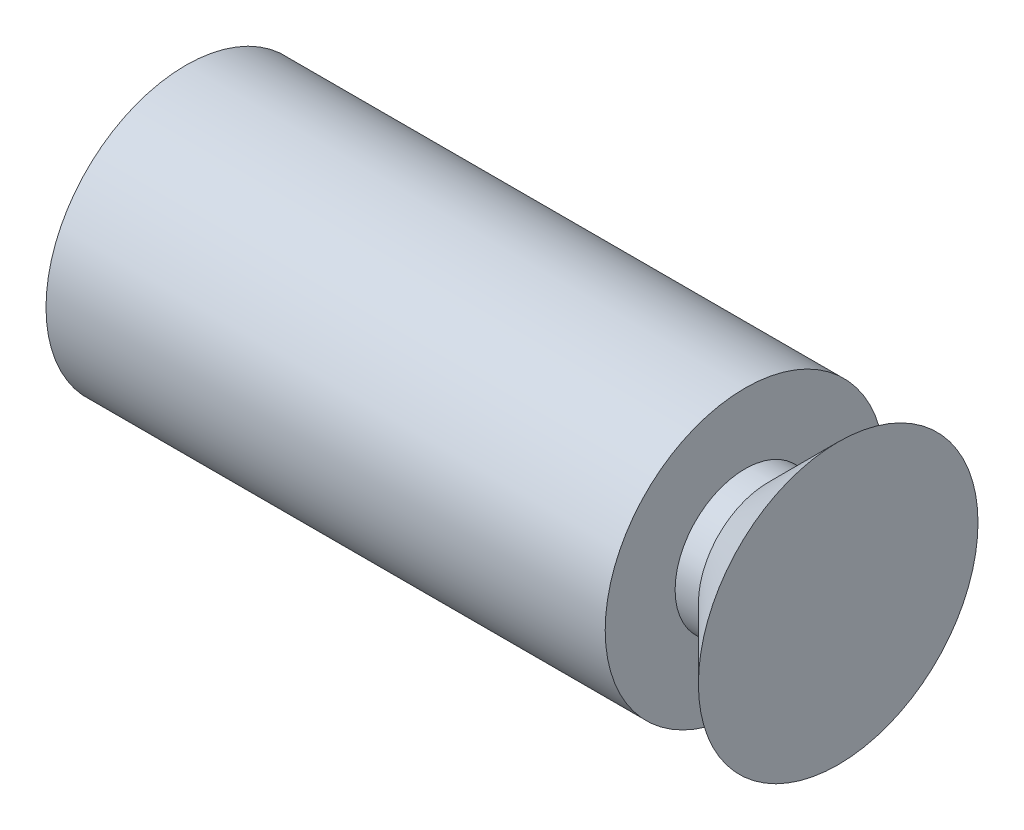
SolidWorks part; units mm, degrees
ref_plane "Спереди" through (0, 0, 0) normal (0, 0, 1) x (1, 0, 0)
ref_plane "Сверху" through (0, 0, 0) normal (0, 1, 0) x (1, 0, 0)
ref_plane "Справа" through (0, 0, 0) normal (1, 0, 0) x (0, 0, -1)
sketch "Эскиз1" plane through (0, 0, 0) normal (0, 0, 1) x (1, 0, 0)
  line L0 (-97.0894, 0) -> (88.796, 0) construction
  line L1 (5.5, 0) -> (5.5, -3)
  line L2 (3.5, -1.5) -> (4, -1.5)
  line L3 (3.5, -1.5) -> (3.5, -3)
  line L4 (3.5, -3) -> (-8.5, -3)
  line L5 (-8.5, -3) -> (-8.5, -1.2)
  line L6 (-8.5, -1.2) -> (-0.5, -1.2)
  line L7 (-0.5, -1.2) -> (0.3, 0)
  line L8 (5.5, 0) -> (0.3, 0)
  line L9 (4, -1.5) -> (5.5, -3)
  dimension "D1" = 3
  dimension "D2" = 1.2
  dimension "D3" = 8
  dimension "D4" = 0.8
  dimension "D5" = 3
  dimension "D6" = 12
  dimension "D7" = 45
  dimension "D8" = 2
revolve "Основание-Повернуть" add sketch "Эскиз1" angle 360 about L0
cosmetic thread "Условное изображение резьбы1"
cosmetic thread "Условное изображение резьбы2"
cosmetic thread "Условное изображение резьбы3"
cosmetic thread "Условное изображение резьбы4"
cosmetic thread "Условное изображение резьбы5"
cosmetic thread "Условное изображение резьбы6"
cosmetic thread "Условное изображение резьбы7"
cosmetic thread "Условное изображение резьбы8"
cosmetic thread "Условное изображение резьбы9"
cosmetic thread "Условное изображение резьбы10"
